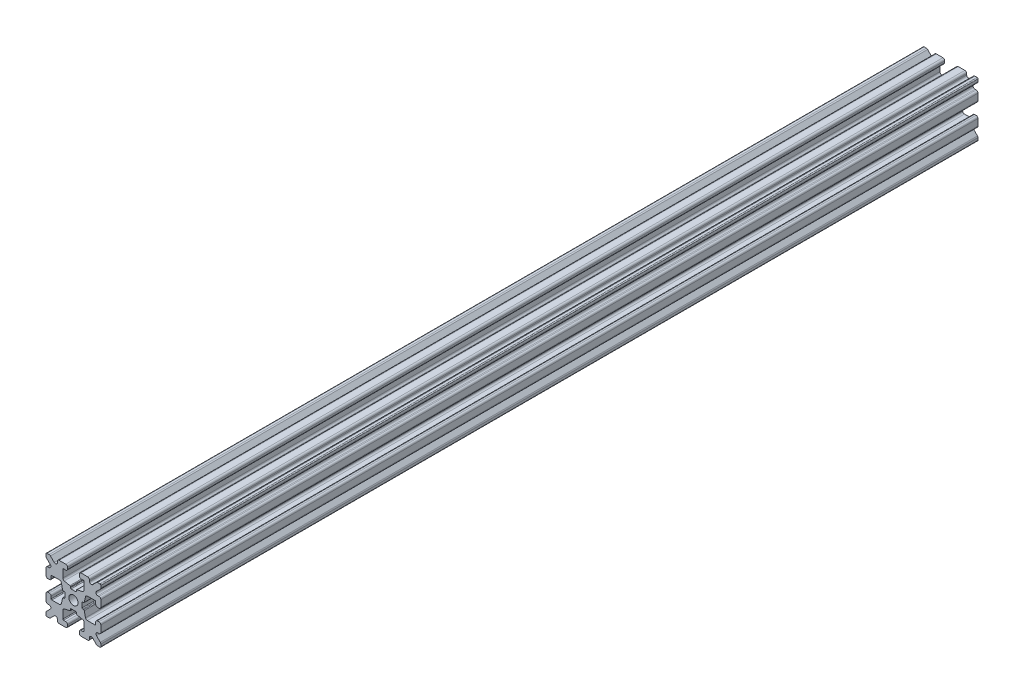
SolidWorks part; units mm, degrees
material "1060 Alloy"
ref_plane "Front Plane" through (0, 0, 0) normal (0, 0, 1) x (1, 0, 0)
ref_plane "Top Plane" through (0, 0, 0) normal (0, 1, 0) x (1, 0, 0)
ref_plane "Right Plane" through (0, 0, 0) normal (1, 0, 0) x (0, 0, -1)
sketch "Sketch1" plane through (0, 0, 0) normal (0, 0, 1) x (1, 0, 0)
  line L1 (-7.5, -7.5) -> (7.5, -7.5)
  line L2 (-7.5, -7.5) -> (-7.5, 7.5)
  line L3 (-7.5, 7.5) -> (7.5, 7.5)
  line L4 (7.5, -7.5) -> (7.5, 7.5)
  line L5 (-7.5, -7.5) -> (7.5, 7.5) construction
  line L6 (-7.5, 7.5) -> (7.5, -7.5) construction
  circle A0 centre (0, 0) radius 1.25
  point P0 (0, 0)
  dimension "D2" = 2.5
  dimension "D1" = 15
extrude "Change length" add sketch "Sketch1" along normal mid plane 240
fillet "Fillet1" radius 0.25 4 edges at (7.5, -7.5, 0) (-7.5, -7.5, 0) (7.5, 7.5, 0) (-7.5, 7.5, 0)
sketch "Sketch2" plane through (0, 0, 120) normal (0, 0, 1) x (1, 0, 0)
  line L0 (-7.5, 7.25) -> (-7.5, -7.25) construction
  line L1 (-7.5, 1.6) -> (-6.1, 1.6)
  line L2 (-7.5, 1.6) -> (-7.5, -1.6)
  line L3 (-7.5, -1.6) -> (-6.1, -1.6)
  line L4 (-6.1, 1.6) -> (-6.1, 2.9)
  line L5 (0, 0) -> (-12.1036, 0) construction
  line L6 (-6.1, -2.9) -> (-3.4, -2.9)
  line L7 (0, 0) -> (-7.25, 7.25) construction
  line L8 (-6.1, 2.9) -> (-3.4, 2.9)
  line L9 (-3.4, -2.9) -> (-3.4, 2.9)
  line L10 (55, 0) -> (-55, 0) construction
  line L11 (-6.1, -2.9) -> (-6.1, -1.6)
  line L12 (2.9, 6.1) -> (1.6, 6.1)
  line L13 (2.9, 3.4) -> (-2.9, 3.4)
  line L14 (-2.9, 6.1) -> (-2.9, 3.4)
  line L15 (2.9, 6.1) -> (2.9, 3.4)
  line L16 (-1.6, 6.1) -> (-2.9, 6.1)
  line L17 (1.6, 7.5) -> (1.6, 6.1)
  line L18 (-1.6, 7.5) -> (1.6, 7.5)
  line L19 (-1.6, 7.5) -> (-1.6, 6.1)
  line L20 (-1.6, -7.5) -> (-1.6, -6.1)
  line L21 (-1.6, -7.5) -> (1.6, -7.5)
  line L22 (1.6, -7.5) -> (1.6, -6.1)
  line L23 (-1.6, -6.1) -> (-2.9, -6.1)
  line L24 (2.9, -6.1) -> (2.9, -3.4)
  line L25 (-2.9, -6.1) -> (-2.9, -3.4)
  line L26 (2.9, -3.4) -> (-2.9, -3.4)
  line L27 (2.9, -6.1) -> (1.6, -6.1)
  line L28 (6.1, -2.9) -> (6.1, -1.6)
  line L29 (3.4, -2.9) -> (3.4, 2.9)
  line L30 (6.1, 2.9) -> (3.4, 2.9)
  line L31 (6.1, -2.9) -> (3.4, -2.9)
  line L32 (6.1, 1.6) -> (6.1, 2.9)
  line L33 (7.5, -1.6) -> (6.1, -1.6)
  line L34 (7.5, 1.6) -> (7.5, -1.6)
  line L35 (7.5, 1.6) -> (6.1, 1.6)
  dimension "D1" = 3.2
  dimension "D2" = 5.8
  dimension "D3" = 1.4
  dimension "D4" = 2.7
extrude "Cut-Extrude1" cut sketch "Sketch2" against normal through all
sketch "Sketch4" plane through (0, 0, 120) normal (0, 0, 1) x (1, 0, 0)
  line L0 (-3.4, 2.9) -> (-2.75, 0)
  line L1 (55, 0) -> (-55, 0) construction
  line L2 (-2.75, 0) -> (-3.4, -2.9)
  line L3 (-3.4, -2.9) -> (-3.4, 2.9) construction
  line L4 (-3.4, 2.9) -> (-3.4, -2.9)
  line L5 (-2.9, 3.4) -> (0, 2.75)
  line L6 (0, 2.75) -> (2.9, 3.4)
  line L7 (2.9, 3.4) -> (-2.9, 3.4)
  line L8 (3.4, 2.9) -> (2.75, 0)
  line L9 (2.75, 0) -> (3.4, -2.9)
  line L10 (3.4, -2.9) -> (3.4, 2.9)
  line L11 (-2.9, -3.4) -> (0, -2.75)
  line L12 (0, -2.75) -> (2.9, -3.4)
  line L13 (2.9, -3.4) -> (-2.9, -3.4)
  circle A2 centre (0, 0) radius 2.75
  circle A3 centre (0, 0) radius 2.75 construction
  dimension "D1" = 1.5
extrude "Cut-Extrude3" cut sketch "Sketch4" against normal through all
fillet "Fillet3" radius 0.5 16 edges at (-6.1, -1.6, 0) (-7.5, -1.6, 0) (-6.1, 1.6, 0) (-7.5, 1.6, 0) (-1.6, -7.5, 0) (-1.6, -6.1, 0) (1.6, -7.5, 0) (1.6, -6.1, 0) (6.1, -1.6, 0) (7.5, -1.6, 0) (7.5, 1.6, 0) (6.1, 1.6, 0) (1.6, 7.5, 0) (1.6, 6.1, 0) (-1.6, 7.5, 0) (-1.6, 6.1, 0)
fillet "Fillet4" radius 0.5 8 edges at (-3.4, 2.9, 0) (-3.4, -2.9, 0) (2.9, -3.4, 0) (-2.9, -3.4, 0) (3.4, -2.9, 0) (3.4, 2.9, 0) (-2.9, 3.4, 0) (2.9, 3.4, 0)
fillet "Fillet5" radius 3 4 edges at (0, -2.75, 0) (2.75, 0, 0) (-2.75, 0, 0) (0, 2.75, 0)
fillet "Fillet6" radius 0.2 8 edges at (-2.9, -6.1, 0) (2.9, -6.1, 0) (6.1, -2.9, 0) (6.1, 2.9, 0) (2.9, 6.1, 0) (-2.9, 6.1, 0) (-6.1, -2.9, 0) (-6.1, 2.9, 0)
sketch "Sketch5" plane through (0, 0, 120) normal (0, 0, 1) x (1, 0, 0)
  line L0 (0, 0) -> (-7.25, 7.25) construction
  line L1 (-7.5, 6.4393) -> (-5.4607, 4.4)
  line L2 (-6.4393, 7.5) -> (-4.4, 5.4607)
  line L3 (-7.5, 4.4) -> (-5.4607, 4.4)
  line L4 (-3.8003, 2.9) -> (-5.9, 2.9) construction
  line L5 (0, 0) -> (-12.1819, 0) construction
  line L6 (-4.4, 7.5) -> (-4.4, 5.4607)
  line L7 (-2.9, 5.9) -> (-2.9, 3.8003) construction
  line L8 (-7.5, 6.4393) -> (-7.5, 4.4)
  line L9 (-7.5, 7.25) -> (-7.5, 2.1) construction
  line L10 (2.1, -7.5) -> (7.25, -7.5) construction
  line L11 (7.5, -7.25) -> (7.5, -2.1) construction
  line L12 (7.25, 7.5) -> (2.1, 7.5) construction
  line L13 (-2.1, 7.5) -> (-7.25, 7.5) construction
  line L14 (-4.4, 7.5) -> (-6.4393, 7.5)
  line L16 (55, 0) -> (-55, 0) construction
  line L17 (0, 0) -> (0, 10.993) construction
  line L18 (0, -54.6431) -> (0, 54.6431) construction
  line L20 (4.4, 7.5) -> (6.4393, 7.5)
  line L22 (7.5, 6.4393) -> (7.5, 4.4)
  line L23 (4.4, 7.5) -> (4.4, 5.4607)
  line L24 (7.5, 4.4) -> (5.4607, 4.4)
  line L25 (6.4393, 7.5) -> (4.4, 5.4607)
  line L26 (7.5, 6.4393) -> (5.4607, 4.4)
  line L27 (7.5, -6.4393) -> (5.4607, -4.4)
  line L28 (6.4393, -7.5) -> (4.4, -5.4607)
  line L29 (7.5, -4.4) -> (5.4607, -4.4)
  line L30 (4.4, -7.5) -> (4.4, -5.4607)
  line L31 (7.5, -6.4393) -> (7.5, -4.4)
  line L33 (4.4, -7.5) -> (6.4393, -7.5)
  line L36 (-4.4, -7.5) -> (-6.4393, -7.5)
  line L38 (-7.5, -6.4393) -> (-7.5, -4.4)
  line L39 (-4.4, -7.5) -> (-4.4, -5.4607)
  line L40 (-7.5, -4.4) -> (-5.4607, -4.4)
  line L41 (-6.4393, -7.5) -> (-4.4, -5.4607)
  line L42 (-7.5, -6.4393) -> (-5.4607, -4.4)
  dimension "D1" = 1.5
  dimension "D2" = 1.5
  dimension "D3" = 1.5
extrude "Cut-Extrude4" cut sketch "Sketch5" against normal through all
fillet "Fillet8" radius 0.5 24 edges at (-5.4607, 4.4, 0) (-7.5, 4.4, 0) (-5.4607, -4.4, 0) (-7.5, -4.4, 0) (-4.4, -7.5, 0) (-4.4, -5.4607, 0) (4.4, -7.5, 0) (4.4, -5.4607, 0) (5.4607, -4.4, 0) (7.5, -4.4, 0) (7.5, 4.4, 0) (5.4607, 4.4, 0) (4.4, 5.4607, 0) (4.4, 7.5, 0) (-4.4, 5.4607, 0) (-4.4, 7.5, 0) (-6.4393, 7.5, 0) (-7.5, 6.4393, 0) (6.4393, 7.5, 0) (7.5, 6.4393, 0) (6.4393, -7.5, 0) (7.5, -6.4393, 0) (-6.4393, -7.5, 0) (-7.5, -6.4393, 0)
sketch "Sketch6" plane through (0, 0, 120) normal (0, 0, 1) x (1, 0, 0)
  line L0 (0, 0) -> (0, 11.013) construction
  line L1 (0.6561, 2.8971) -> (2.1235, 2.8971) construction
  line L2 (0, -54.6431) -> (0, 54.6431) construction
  line L3 (0, 0) -> (7.25, 7.25) construction
  line L4 (7.5, 0.8255) -> (7.5, -0.8255)
  line L5 (2.3471, 0.8255) -> (7.5, 0.8255)
  line L6 (0, 0) -> (12.4016, 0) construction
  line L7 (0.8255, -7.5) -> (-0.8255, -7.5)
  line L8 (2.3471, -0.8255) -> (2.3471, 0.8255)
  line L9 (0.8255, -2.3471) -> (0.8255, -7.5)
  line L10 (7.5, -0.8255) -> (2.3471, -0.8255)
  line L11 (-7.5, -0.8255) -> (-2.3471, -0.8255)
  line L12 (-2.3471, -0.8255) -> (-2.3471, 0.8255)
  line L13 (-0.8255, -2.3471) -> (0.8255, -2.3471)
  line L14 (-0.8255, 7.5) -> (-0.8255, 2.3471)
  line L15 (-0.8255, 2.3471) -> (0.8255, 2.3471)
  line L16 (-0.8255, -7.5) -> (-0.8255, -2.3471)
  line L17 (0.8255, 2.3471) -> (0.8255, 7.5)
  line L18 (0.8255, 7.5) -> (-0.8255, 7.5)
  line L19 (3.9, 7.5) -> (2.1, 7.5) construction
  line L20 (-2.3471, 0.8255) -> (-7.5, 0.8255)
  line L21 (-7.5, 0.8255) -> (-7.5, -0.8255)
  point P5 (0, -2.5973)
  point P7 (0, 2.5973)
  dimension "D3" = 0.55
  dimension "D1" = 1.651
extrude "Cut-Extrude5" cut sketch "Sketch6" against normal through all
fillet "Fillet10" radius 0.2 16 edges at (-2.935, 0.8255, 0) (-2.935, -0.8255, 0) (2.935, -0.8255, 0) (2.935, 0.8255, 0) (0.8255, 2.935, 0) (-0.8255, 2.935, 0) (-2.3471, 0.8255, 0) (-2.3471, -0.8255, 0) (0.8255, 2.3471, 0) (-0.8255, 2.3471, 0) (2.3471, 0.8255, 0) (2.3471, -0.8255, 0) (0.8255, -2.935, 0) (0.8255, -2.3471, 0) (-0.8255, -2.3471, 0) (-0.8255, -2.935, 0)
